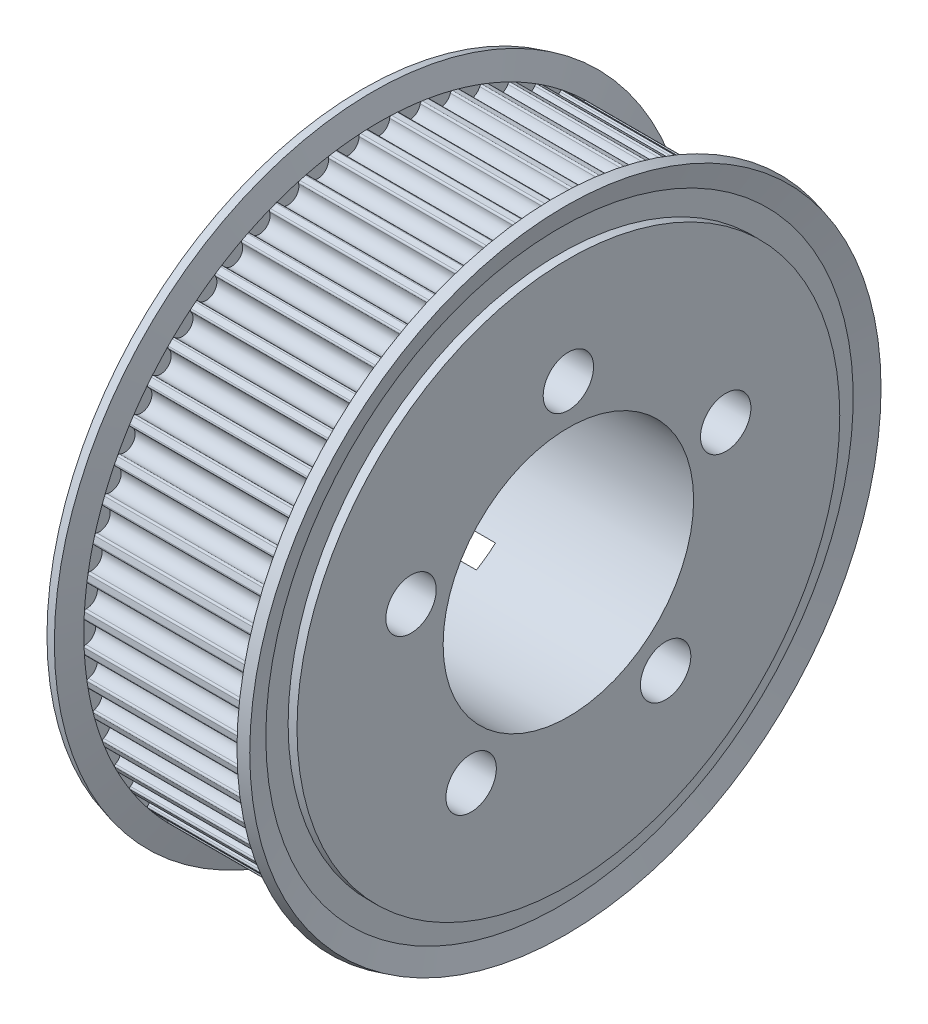
SolidWorks part; units mm, degrees
ref_plane "Front Plane" through (0, 0, 0) normal (0, 0, 1) x (1, 0, 0)
ref_plane "Top Plane" through (0, 0, 0) normal (0, 1, 0) x (1, 0, 0)
ref_plane "Right Plane" through (0, 0, 0) normal (1, 0, 0) x (0, 0, -1)
ref_plane "Plane1" through (0, 0, 0) normal (0, 0, 1) x (1, 0, 0)
sketch "Sketch1" plane through (0, 0, 0) normal (0, 0, 1) x (1, 0, 0)
  line L0 (0, 0) -> (0, 26)
  line L1 (0, 26) -> (0.85, 26)
  line L2 (0.85, 26) -> (0.85, 28.1383)
  line L3 (0.85, 28.1383) -> (0.2865, 30.2412)
  line L4 (0.2865, 30.2412) -> (1.2525, 30.5)
  line L5 (1.2525, 30.5) -> (1.85, 28.27)
  line L6 (1.85, 28.27) -> (18.15, 28.27)
  line L7 (18.15, 28.27) -> (18.7475, 30.5)
  line L8 (18.7475, 30.5) -> (19.7135, 30.2412)
  line L9 (19.7135, 30.2412) -> (19.15, 28.1383)
  line L10 (19.15, 28.1383) -> (19.15, 26)
  line L11 (19.15, 26) -> (20, 26)
  line L12 (20, 26) -> (20, 0)
  line L13 (20, 0) -> (0, 0)
  line L14 (20, 0) -> (0, 0) construction
revolve "Revolve1" add sketch "Sketch1" angle 360 about L14
ref_plane "Plane2" through (10, 0, 0) normal (1, 0, 0) x (0, 0, -1)
sketch "Sketch2" plane through (10, 0, 0) normal (1, 0, 0) x (0, 0, -1)
  line L0 (-1.2204, 28.624) -> (-1.2042, 28.2443)
  line L1 (1.2042, 28.2443) -> (1.2204, 28.624)
  arc A0 (-1.2042, 28.2443) -> (-1.0274, 28.0866) centre (-1.1969, 28.0745) cw
  arc A1 (-1.0274, 28.0866) -> (1.0274, 28.0866) centre (0, 28.16) ccw
  arc A2 (1.0274, 28.0866) -> (1.2042, 28.2443) centre (1.1969, 28.0745) cw
  arc A3 (1.2204, 28.624) -> (-1.2204, 28.624) centre (0, 0) ccw
extrude "Cut-Extrude1" cut sketch "Sketch2" against normal blind 8.15 and the other way blind 8.15
ref_plane "Plane3" through (10, 0, 0) normal (1, 0, 0) x (0, 0, -1)
sketch "Sketch3" plane through (10, 0, 0) normal (1, 0, 0) x (0, 0, -1)
  line L0 (-4.2057, 28.3396) -> (-4.1499, 27.9637)
  line L1 (-1.7547, 28.2155) -> (-1.7783, 28.5948)
  arc A0 (-4.1499, 27.9637) -> (-3.9576, 27.8254) centre (-4.125, 27.7956) cw
  arc A1 (-3.9576, 27.8254) -> (-1.9141, 28.0401) centre (-2.9435, 28.0057) ccw
  arc A2 (-1.9141, 28.0401) -> (-1.7547, 28.2155) centre (-1.7442, 28.0458) cw
  arc A3 (-1.7783, 28.5948) -> (-4.2057, 28.3396) centre (0, 0) ccw
extrude "Cut-Extrude2" cut sketch "Sketch3" against normal blind 8.15 and the other way blind 8.15
ref_plane "Plane4" through (10, 0, 0) normal (1, 0, 0) x (0, 0, -1)
sketch "Sketch4" plane through (10, 0, 0) normal (1, 0, 0) x (0, 0, -1)
  line L0 (-7.145, 27.7448) -> (-7.0502, 27.3768)
  line L1 (-4.6945, 27.8775) -> (-4.7576, 28.2522)
  arc A0 (-7.0502, 27.3768) -> (-6.8445, 27.2592) centre (-7.0078, 27.2121) cw
  arc A1 (-6.8445, 27.2592) -> (-4.8346, 27.6865) centre (-5.8548, 27.5446) ccw
  arc A2 (-4.8346, 27.6865) -> (-4.6945, 27.8775) centre (-4.6662, 27.7099) cw
  arc A3 (-4.7576, 28.2522) -> (-7.145, 27.7448) centre (0, 0) ccw
extrude "Cut-Extrude3" cut sketch "Sketch4" against normal blind 8.15 and the other way blind 8.15
ref_plane "Plane5" through (10, 0, 0) normal (1, 0, 0) x (0, 0, -1)
sketch "Sketch5" plane through (10, 0, 0) normal (1, 0, 0) x (0, 0, -1)
  line L0 (-10.0059, 26.8459) -> (-9.8732, 26.4898)
  line L1 (-7.5827, 27.2341) -> (-7.6847, 27.6002)
  arc A0 (-9.8732, 26.4898) -> (-9.6563, 26.3945) centre (-9.8139, 26.3306) cw
  arc A1 (-9.6563, 26.3945) -> (-7.7021, 27.0294) centre (-8.7019, 26.7818) ccw
  arc A2 (-7.7021, 27.0294) -> (-7.5827, 27.2341) centre (-7.5371, 27.0703) cw
  arc A3 (-7.6847, 27.6002) -> (-10.0059, 26.8459) centre (0, 0) ccw
extrude "Cut-Extrude4" cut sketch "Sketch5" against normal blind 8.15 and the other way blind 8.15
ref_plane "Plane6" through (10, 0, 0) normal (1, 0, 0) x (0, 0, -1)
sketch "Sketch6" plane through (10, 0, 0) normal (1, 0, 0) x (0, 0, -1)
  line L0 (-12.7573, 25.6529) -> (-12.5881, 25.3127)
  line L1 (-10.3879, 26.2923) -> (-10.5276, 26.6457)
  arc A0 (-12.5881, 25.3127) -> (-12.3624, 25.2405) centre (-12.5124, 25.1605) cw
  arc A1 (-12.3624, 25.2405) -> (-10.4853, 26.0763) centre (-11.4537, 25.7254) ccw
  arc A2 (-10.4853, 26.0763) -> (-10.3879, 26.2923) centre (-10.3255, 26.1342) cw
  arc A3 (-10.5276, 26.6457) -> (-12.7573, 25.6529) centre (0, 0) ccw
extrude "Cut-Extrude5" cut sketch "Sketch6" against normal blind 8.15 and the other way blind 8.15
ref_plane "Plane7" through (10, 0, 0) normal (1, 0, 0) x (0, 0, -1)
sketch "Sketch7" plane through (10, 0, 0) normal (1, 0, 0) x (0, 0, -1)
  line L0 (-15.3689, 24.1789) -> (-15.165, 23.8582)
  line L1 (-13.0793, 25.0624) -> (-13.2551, 25.3993)
  arc A0 (-15.165, 23.8582) -> (-14.933, 23.81) centre (-15.0738, 23.7148) cw
  arc A1 (-14.933, 23.81) -> (-13.1536, 24.8374) centre (-14.08, 24.3873) ccw
  arc A2 (-13.1536, 24.8374) -> (-13.0793, 25.0624) centre (-13.0007, 24.9117) cw
  arc A3 (-13.2551, 25.3993) -> (-15.3689, 24.1789) centre (0, 0) ccw
extrude "Cut-Extrude6" cut sketch "Sketch7" against normal blind 8.15 and the other way blind 8.15
ref_plane "Plane8" through (10, 0, 0) normal (1, 0, 0) x (0, 0, -1)
sketch "Sketch8" plane through (10, 0, 0) normal (1, 0, 0) x (0, 0, -1)
  line L0 (-17.8121, 22.44) -> (-17.5758, 22.1423)
  line L1 (-15.6274, 23.558) -> (-15.8375, 23.8746)
  arc A0 (-17.5758, 22.1423) -> (-17.3401, 22.1187) centre (-17.4701, 22.0092) cw
  arc A1 (-17.3401, 22.1187) -> (-15.6777, 23.3264) centre (-16.552, 22.7819) ccw
  arc A2 (-15.6777, 23.3264) -> (-15.6274, 23.558) centre (-15.5334, 23.4163) cw
  arc A3 (-15.8375, 23.8746) -> (-17.8121, 22.44) centre (0, 0) ccw
extrude "Cut-Extrude7" cut sketch "Sketch8" against normal blind 8.15 and the other way blind 8.15
ref_plane "Plane9" through (10, 0, 0) normal (1, 0, 0) x (0, 0, -1)
sketch "Sketch9" plane through (10, 0, 0) normal (1, 0, 0) x (0, 0, -1)
  line L0 (-20.0601, 20.4552) -> (-19.794, 20.1839)
  line L1 (-18.0043, 21.7954) -> (-18.2463, 22.0884)
  arc A0 (-19.794, 20.1839) -> (-19.5571, 20.185) centre (-19.675, 20.0625) cw
  arc A1 (-19.5571, 20.185) -> (-18.0301, 21.5599) centre (-18.8427, 20.927) ccw
  arc A2 (-18.0301, 21.5599) -> (-18.0043, 21.7954) centre (-17.896, 21.6643) cw
  arc A3 (-18.2463, 22.0884) -> (-20.0601, 20.4552) centre (0, 0) ccw
extrude "Cut-Extrude8" cut sketch "Sketch9" against normal blind 8.15 and the other way blind 8.15
ref_plane "Plane10" through (10, 0, 0) normal (1, 0, 0) x (0, 0, -1)
sketch "Sketch10" plane through (10, 0, 0) normal (1, 0, 0) x (0, 0, -1)
  line L0 (-22.0884, 18.2463) -> (-21.7954, 18.0043)
  line L1 (-20.1839, 19.794) -> (-20.4552, 20.0601)
  arc A0 (-21.7954, 18.0043) -> (-21.5599, 18.0301) centre (-21.6643, 17.896) cw
  arc A1 (-21.5599, 18.0301) -> (-20.185, 19.5571) centre (-20.927, 18.8427) ccw
  arc A2 (-20.185, 19.5571) -> (-20.1839, 19.794) centre (-20.0625, 19.675) cw
  arc A3 (-20.4552, 20.0601) -> (-22.0884, 18.2463) centre (0, 0) ccw
extrude "Cut-Extrude9" cut sketch "Sketch10" against normal blind 8.15 and the other way blind 8.15
ref_plane "Plane11" through (10, 0, 0) normal (1, 0, 0) x (0, 0, -1)
sketch "Sketch11" plane through (10, 0, 0) normal (1, 0, 0) x (0, 0, -1)
  line L0 (-23.8746, 15.8375) -> (-23.558, 15.6274)
  line L1 (-22.1423, 17.5758) -> (-22.44, 17.8121)
  arc A0 (-23.558, 15.6274) -> (-23.3264, 15.6777) centre (-23.4163, 15.5334) cw
  arc A1 (-23.3264, 15.6777) -> (-22.1187, 17.3401) centre (-22.7819, 16.552) ccw
  arc A2 (-22.1187, 17.3401) -> (-22.1423, 17.5758) centre (-22.0092, 17.4701) cw
  arc A3 (-22.44, 17.8121) -> (-23.8746, 15.8375) centre (0, 0) ccw
extrude "Cut-Extrude10" cut sketch "Sketch11" against normal blind 8.15 and the other way blind 8.15
ref_plane "Plane12" through (10, 0, 0) normal (1, 0, 0) x (0, 0, -1)
sketch "Sketch12" plane through (10, 0, 0) normal (1, 0, 0) x (0, 0, -1)
  line L0 (-25.3993, 13.2551) -> (-25.0624, 13.0793)
  line L1 (-23.8582, 15.165) -> (-24.1789, 15.3689)
  arc A0 (-25.0624, 13.0793) -> (-24.8374, 13.1536) centre (-24.9117, 13.0007) cw
  arc A1 (-24.8374, 13.1536) -> (-23.81, 14.933) centre (-24.3873, 14.08) ccw
  arc A2 (-23.81, 14.933) -> (-23.8582, 15.165) centre (-23.7148, 15.0738) cw
  arc A3 (-24.1789, 15.3689) -> (-25.3993, 13.2551) centre (0, 0) ccw
extrude "Cut-Extrude11" cut sketch "Sketch12" against normal blind 8.15 and the other way blind 8.15
ref_plane "Plane13" through (10, 0, 0) normal (1, 0, 0) x (0, 0, -1)
sketch "Sketch13" plane through (10, 0, 0) normal (1, 0, 0) x (0, 0, -1)
  line L0 (-26.6457, 10.5276) -> (-26.2923, 10.3879)
  line L1 (-25.3127, 12.5881) -> (-25.6529, 12.7573)
  arc A0 (-26.2923, 10.3879) -> (-26.0763, 10.4853) centre (-26.1342, 10.3255) cw
  arc A1 (-26.0763, 10.4853) -> (-25.2405, 12.3624) centre (-25.7254, 11.4537) ccw
  arc A2 (-25.2405, 12.3624) -> (-25.3127, 12.5881) centre (-25.1605, 12.5124) cw
  arc A3 (-25.6529, 12.7573) -> (-26.6457, 10.5276) centre (0, 0) ccw
extrude "Cut-Extrude12" cut sketch "Sketch13" against normal blind 8.15 and the other way blind 8.15
ref_plane "Plane14" through (10, 0, 0) normal (1, 0, 0) x (0, 0, -1)
sketch "Sketch14" plane through (10, 0, 0) normal (1, 0, 0) x (0, 0, -1)
  line L0 (-27.6002, 7.6847) -> (-27.2341, 7.5827)
  line L1 (-26.4898, 9.8732) -> (-26.8459, 10.0059)
  arc A0 (-27.2341, 7.5827) -> (-27.0294, 7.7021) centre (-27.0703, 7.5371) cw
  arc A1 (-27.0294, 7.7021) -> (-26.3945, 9.6563) centre (-26.7818, 8.7019) ccw
  arc A2 (-26.3945, 9.6563) -> (-26.4898, 9.8732) centre (-26.3306, 9.8139) cw
  arc A3 (-26.8459, 10.0059) -> (-27.6002, 7.6847) centre (0, 0) ccw
extrude "Cut-Extrude13" cut sketch "Sketch14" against normal blind 8.15 and the other way blind 8.15
ref_plane "Plane15" through (10, 0, 0) normal (1, 0, 0) x (0, 0, -1)
sketch "Sketch15" plane through (10, 0, 0) normal (1, 0, 0) x (0, 0, -1)
  line L0 (-28.2522, 4.7576) -> (-27.8775, 4.6945)
  line L1 (-27.3768, 7.0502) -> (-27.7448, 7.145)
  arc A0 (-27.8775, 4.6945) -> (-27.6865, 4.8346) centre (-27.7099, 4.6662) cw
  arc A1 (-27.6865, 4.8346) -> (-27.2592, 6.8445) centre (-27.5446, 5.8548) ccw
  arc A2 (-27.2592, 6.8445) -> (-27.3768, 7.0502) centre (-27.2121, 7.0078) cw
  arc A3 (-27.7448, 7.145) -> (-28.2522, 4.7576) centre (0, 0) ccw
extrude "Cut-Extrude14" cut sketch "Sketch15" against normal blind 8.15 and the other way blind 8.15
ref_plane "Plane16" through (10, 0, 0) normal (1, 0, 0) x (0, 0, -1)
sketch "Sketch16" plane through (10, 0, 0) normal (1, 0, 0) x (0, 0, -1)
  line L0 (-28.5948, 1.7783) -> (-28.2155, 1.7547)
  line L1 (-27.9637, 4.1499) -> (-28.3396, 4.2057)
  arc A0 (-28.2155, 1.7547) -> (-28.0401, 1.9141) centre (-28.0458, 1.7442) cw
  arc A1 (-28.0401, 1.9141) -> (-27.8254, 3.9576) centre (-28.0057, 2.9435) ccw
  arc A2 (-27.8254, 3.9576) -> (-27.9637, 4.1499) centre (-27.7956, 4.125) cw
  arc A3 (-28.3396, 4.2057) -> (-28.5948, 1.7783) centre (0, 0) ccw
extrude "Cut-Extrude15" cut sketch "Sketch16" against normal blind 8.15 and the other way blind 8.15
ref_plane "Plane17" through (10, 0, 0) normal (1, 0, 0) x (0, 0, -1)
sketch "Sketch17" plane through (10, 0, 0) normal (1, 0, 0) x (0, 0, -1)
  line L0 (-28.624, -1.2204) -> (-28.2443, -1.2042)
  line L1 (-28.2443, 1.2042) -> (-28.624, 1.2204)
  arc A0 (-28.2443, -1.2042) -> (-28.0866, -1.0274) centre (-28.0745, -1.1969) cw
  arc A1 (-28.0866, -1.0274) -> (-28.0866, 1.0274) centre (-28.16, 0) ccw
  arc A2 (-28.0866, 1.0274) -> (-28.2443, 1.2042) centre (-28.0745, 1.1969) cw
  arc A3 (-28.624, 1.2204) -> (-28.624, -1.2204) centre (0, 0) ccw
extrude "Cut-Extrude16" cut sketch "Sketch17" against normal blind 8.15 and the other way blind 8.15
ref_plane "Plane18" through (10, 0, 0) normal (1, 0, 0) x (0, 0, -1)
sketch "Sketch18" plane through (10, 0, 0) normal (1, 0, 0) x (0, 0, -1)
  line L0 (-28.3396, -4.2057) -> (-27.9637, -4.1499)
  line L1 (-28.2155, -1.7547) -> (-28.5948, -1.7783)
  arc A0 (-27.9637, -4.1499) -> (-27.8254, -3.9576) centre (-27.7956, -4.125) cw
  arc A1 (-27.8254, -3.9576) -> (-28.0401, -1.9141) centre (-28.0057, -2.9435) ccw
  arc A2 (-28.0401, -1.9141) -> (-28.2155, -1.7547) centre (-28.0458, -1.7442) cw
  arc A3 (-28.5948, -1.7783) -> (-28.3396, -4.2057) centre (0, 0) ccw
extrude "Cut-Extrude17" cut sketch "Sketch18" against normal blind 8.15 and the other way blind 8.15
ref_plane "Plane19" through (10, 0, 0) normal (1, 0, 0) x (0, 0, -1)
sketch "Sketch19" plane through (10, 0, 0) normal (1, 0, 0) x (0, 0, -1)
  line L0 (-27.7448, -7.145) -> (-27.3768, -7.0502)
  line L1 (-27.8775, -4.6945) -> (-28.2522, -4.7576)
  arc A0 (-27.3768, -7.0502) -> (-27.2592, -6.8445) centre (-27.2121, -7.0078) cw
  arc A1 (-27.2592, -6.8445) -> (-27.6865, -4.8346) centre (-27.5446, -5.8548) ccw
  arc A2 (-27.6865, -4.8346) -> (-27.8775, -4.6945) centre (-27.7099, -4.6662) cw
  arc A3 (-28.2522, -4.7576) -> (-27.7448, -7.145) centre (0, 0) ccw
extrude "Cut-Extrude18" cut sketch "Sketch19" against normal blind 8.15 and the other way blind 8.15
ref_plane "Plane20" through (10, 0, 0) normal (1, 0, 0) x (0, 0, -1)
sketch "Sketch20" plane through (10, 0, 0) normal (1, 0, 0) x (0, 0, -1)
  line L0 (-26.8459, -10.0059) -> (-26.4898, -9.8732)
  line L1 (-27.2341, -7.5827) -> (-27.6002, -7.6847)
  arc A0 (-26.4898, -9.8732) -> (-26.3945, -9.6563) centre (-26.3306, -9.8139) cw
  arc A1 (-26.3945, -9.6563) -> (-27.0294, -7.7021) centre (-26.7818, -8.7019) ccw
  arc A2 (-27.0294, -7.7021) -> (-27.2341, -7.5827) centre (-27.0703, -7.5371) cw
  arc A3 (-27.6002, -7.6847) -> (-26.8459, -10.0059) centre (0, 0) ccw
extrude "Cut-Extrude19" cut sketch "Sketch20" against normal blind 8.15 and the other way blind 8.15
ref_plane "Plane21" through (10, 0, 0) normal (1, 0, 0) x (0, 0, -1)
sketch "Sketch21" plane through (10, 0, 0) normal (1, 0, 0) x (0, 0, -1)
  line L0 (-25.6529, -12.7573) -> (-25.3127, -12.5881)
  line L1 (-26.2923, -10.3879) -> (-26.6457, -10.5276)
  arc A0 (-25.3127, -12.5881) -> (-25.2405, -12.3624) centre (-25.1605, -12.5124) cw
  arc A1 (-25.2405, -12.3624) -> (-26.0763, -10.4853) centre (-25.7254, -11.4537) ccw
  arc A2 (-26.0763, -10.4853) -> (-26.2923, -10.3879) centre (-26.1342, -10.3255) cw
  arc A3 (-26.6457, -10.5276) -> (-25.6529, -12.7573) centre (0, 0) ccw
extrude "Cut-Extrude20" cut sketch "Sketch21" against normal blind 8.15 and the other way blind 8.15
ref_plane "Plane22" through (10, 0, 0) normal (1, 0, 0) x (0, 0, -1)
sketch "Sketch22" plane through (10, 0, 0) normal (1, 0, 0) x (0, 0, -1)
  line L0 (-24.1789, -15.3689) -> (-23.8582, -15.165)
  line L1 (-25.0624, -13.0793) -> (-25.3993, -13.2551)
  arc A0 (-23.8582, -15.165) -> (-23.81, -14.933) centre (-23.7148, -15.0738) cw
  arc A1 (-23.81, -14.933) -> (-24.8374, -13.1536) centre (-24.3873, -14.08) ccw
  arc A2 (-24.8374, -13.1536) -> (-25.0624, -13.0793) centre (-24.9117, -13.0007) cw
  arc A3 (-25.3993, -13.2551) -> (-24.1789, -15.3689) centre (0, 0) ccw
extrude "Cut-Extrude21" cut sketch "Sketch22" against normal blind 8.15 and the other way blind 8.15
ref_plane "Plane23" through (10, 0, 0) normal (1, 0, 0) x (0, 0, -1)
sketch "Sketch23" plane through (10, 0, 0) normal (1, 0, 0) x (0, 0, -1)
  line L0 (-22.44, -17.8121) -> (-22.1423, -17.5758)
  line L1 (-23.558, -15.6274) -> (-23.8746, -15.8375)
  arc A0 (-22.1423, -17.5758) -> (-22.1187, -17.3401) centre (-22.0092, -17.4701) cw
  arc A1 (-22.1187, -17.3401) -> (-23.3264, -15.6777) centre (-22.7819, -16.552) ccw
  arc A2 (-23.3264, -15.6777) -> (-23.558, -15.6274) centre (-23.4163, -15.5334) cw
  arc A3 (-23.8746, -15.8375) -> (-22.44, -17.8121) centre (0, 0) ccw
extrude "Cut-Extrude22" cut sketch "Sketch23" against normal blind 8.15 and the other way blind 8.15
ref_plane "Plane24" through (10, 0, 0) normal (1, 0, 0) x (0, 0, -1)
sketch "Sketch24" plane through (10, 0, 0) normal (1, 0, 0) x (0, 0, -1)
  line L0 (-20.4552, -20.0601) -> (-20.1839, -19.794)
  line L1 (-21.7954, -18.0043) -> (-22.0884, -18.2463)
  arc A0 (-20.1839, -19.794) -> (-20.185, -19.5571) centre (-20.0625, -19.675) cw
  arc A1 (-20.185, -19.5571) -> (-21.5599, -18.0301) centre (-20.927, -18.8427) ccw
  arc A2 (-21.5599, -18.0301) -> (-21.7954, -18.0043) centre (-21.6643, -17.896) cw
  arc A3 (-22.0884, -18.2463) -> (-20.4552, -20.0601) centre (0, 0) ccw
extrude "Cut-Extrude23" cut sketch "Sketch24" against normal blind 8.15 and the other way blind 8.15
ref_plane "Plane25" through (10, 0, 0) normal (1, 0, 0) x (0, 0, -1)
sketch "Sketch25" plane through (10, 0, 0) normal (1, 0, 0) x (0, 0, -1)
  line L0 (-18.2463, -22.0884) -> (-18.0043, -21.7954)
  line L1 (-19.794, -20.1839) -> (-20.0601, -20.4552)
  arc A0 (-18.0043, -21.7954) -> (-18.0301, -21.5599) centre (-17.896, -21.6643) cw
  arc A1 (-18.0301, -21.5599) -> (-19.5571, -20.185) centre (-18.8427, -20.927) ccw
  arc A2 (-19.5571, -20.185) -> (-19.794, -20.1839) centre (-19.675, -20.0625) cw
  arc A3 (-20.0601, -20.4552) -> (-18.2463, -22.0884) centre (0, 0) ccw
extrude "Cut-Extrude24" cut sketch "Sketch25" against normal blind 8.15 and the other way blind 8.15
ref_plane "Plane26" through (10, 0, 0) normal (1, 0, 0) x (0, 0, -1)
sketch "Sketch26" plane through (10, 0, 0) normal (1, 0, 0) x (0, 0, -1)
  line L0 (-15.8375, -23.8746) -> (-15.6274, -23.558)
  line L1 (-17.5758, -22.1423) -> (-17.8121, -22.44)
  arc A0 (-15.6274, -23.558) -> (-15.6777, -23.3264) centre (-15.5334, -23.4163) cw
  arc A1 (-15.6777, -23.3264) -> (-17.3401, -22.1187) centre (-16.552, -22.7819) ccw
  arc A2 (-17.3401, -22.1187) -> (-17.5758, -22.1423) centre (-17.4701, -22.0092) cw
  arc A3 (-17.8121, -22.44) -> (-15.8375, -23.8746) centre (0, 0) ccw
extrude "Cut-Extrude25" cut sketch "Sketch26" against normal blind 8.15 and the other way blind 8.15
ref_plane "Plane27" through (10, 0, 0) normal (1, 0, 0) x (0, 0, -1)
sketch "Sketch27" plane through (10, 0, 0) normal (1, 0, 0) x (0, 0, -1)
  line L0 (-13.2551, -25.3993) -> (-13.0793, -25.0624)
  line L1 (-15.165, -23.8582) -> (-15.3689, -24.1789)
  arc A0 (-13.0793, -25.0624) -> (-13.1536, -24.8374) centre (-13.0007, -24.9117) cw
  arc A1 (-13.1536, -24.8374) -> (-14.933, -23.81) centre (-14.08, -24.3873) ccw
  arc A2 (-14.933, -23.81) -> (-15.165, -23.8582) centre (-15.0738, -23.7148) cw
  arc A3 (-15.3689, -24.1789) -> (-13.2551, -25.3993) centre (0, 0) ccw
extrude "Cut-Extrude26" cut sketch "Sketch27" against normal blind 8.15 and the other way blind 8.15
ref_plane "Plane28" through (10, 0, 0) normal (1, 0, 0) x (0, 0, -1)
sketch "Sketch28" plane through (10, 0, 0) normal (1, 0, 0) x (0, 0, -1)
  line L0 (-10.5276, -26.6457) -> (-10.3879, -26.2923)
  line L1 (-12.5881, -25.3127) -> (-12.7573, -25.6529)
  arc A0 (-10.3879, -26.2923) -> (-10.4853, -26.0763) centre (-10.3255, -26.1342) cw
  arc A1 (-10.4853, -26.0763) -> (-12.3624, -25.2405) centre (-11.4537, -25.7254) ccw
  arc A2 (-12.3624, -25.2405) -> (-12.5881, -25.3127) centre (-12.5124, -25.1605) cw
  arc A3 (-12.7573, -25.6529) -> (-10.5276, -26.6457) centre (0, 0) ccw
extrude "Cut-Extrude27" cut sketch "Sketch28" against normal blind 8.15 and the other way blind 8.15
ref_plane "Plane29" through (10, 0, 0) normal (1, 0, 0) x (0, 0, -1)
sketch "Sketch29" plane through (10, 0, 0) normal (1, 0, 0) x (0, 0, -1)
  line L0 (-7.6847, -27.6002) -> (-7.5827, -27.2341)
  line L1 (-9.8732, -26.4898) -> (-10.0059, -26.8459)
  arc A0 (-7.5827, -27.2341) -> (-7.7021, -27.0294) centre (-7.5371, -27.0703) cw
  arc A1 (-7.7021, -27.0294) -> (-9.6563, -26.3945) centre (-8.7019, -26.7818) ccw
  arc A2 (-9.6563, -26.3945) -> (-9.8732, -26.4898) centre (-9.8139, -26.3306) cw
  arc A3 (-10.0059, -26.8459) -> (-7.6847, -27.6002) centre (0, 0) ccw
extrude "Cut-Extrude28" cut sketch "Sketch29" against normal blind 8.15 and the other way blind 8.15
ref_plane "Plane30" through (10, 0, 0) normal (1, 0, 0) x (0, 0, -1)
sketch "Sketch30" plane through (10, 0, 0) normal (1, 0, 0) x (0, 0, -1)
  line L0 (-4.7576, -28.2522) -> (-4.6945, -27.8775)
  line L1 (-7.0502, -27.3768) -> (-7.145, -27.7448)
  arc A0 (-4.6945, -27.8775) -> (-4.8346, -27.6865) centre (-4.6662, -27.7099) cw
  arc A1 (-4.8346, -27.6865) -> (-6.8445, -27.2592) centre (-5.8548, -27.5446) ccw
  arc A2 (-6.8445, -27.2592) -> (-7.0502, -27.3768) centre (-7.0078, -27.2121) cw
  arc A3 (-7.145, -27.7448) -> (-4.7576, -28.2522) centre (0, 0) ccw
extrude "Cut-Extrude29" cut sketch "Sketch30" against normal blind 8.15 and the other way blind 8.15
ref_plane "Plane31" through (10, 0, 0) normal (1, 0, 0) x (0, 0, -1)
sketch "Sketch31" plane through (10, 0, 0) normal (1, 0, 0) x (0, 0, -1)
  line L0 (-1.7783, -28.5948) -> (-1.7547, -28.2155)
  line L1 (-4.1499, -27.9637) -> (-4.2057, -28.3396)
  arc A0 (-1.7547, -28.2155) -> (-1.9141, -28.0401) centre (-1.7442, -28.0458) cw
  arc A1 (-1.9141, -28.0401) -> (-3.9576, -27.8254) centre (-2.9435, -28.0057) ccw
  arc A2 (-3.9576, -27.8254) -> (-4.1499, -27.9637) centre (-4.125, -27.7956) cw
  arc A3 (-4.2057, -28.3396) -> (-1.7783, -28.5948) centre (0, 0) ccw
extrude "Cut-Extrude30" cut sketch "Sketch31" against normal blind 8.15 and the other way blind 8.15
ref_plane "Plane32" through (10, 0, 0) normal (1, 0, 0) x (0, 0, -1)
sketch "Sketch32" plane through (10, 0, 0) normal (1, 0, 0) x (0, 0, -1)
  line L0 (1.2204, -28.624) -> (1.2042, -28.2443)
  line L1 (-1.2042, -28.2443) -> (-1.2204, -28.624)
  arc A0 (1.2042, -28.2443) -> (1.0274, -28.0866) centre (1.1969, -28.0745) cw
  arc A1 (1.0274, -28.0866) -> (-1.0274, -28.0866) centre (0, -28.16) ccw
  arc A2 (-1.0274, -28.0866) -> (-1.2042, -28.2443) centre (-1.1969, -28.0745) cw
  arc A3 (-1.2204, -28.624) -> (1.2204, -28.624) centre (0, 0) ccw
extrude "Cut-Extrude31" cut sketch "Sketch32" against normal blind 8.15 and the other way blind 8.15
ref_plane "Plane33" through (10, 0, 0) normal (1, 0, 0) x (0, 0, -1)
sketch "Sketch33" plane through (10, 0, 0) normal (1, 0, 0) x (0, 0, -1)
  line L0 (4.2057, -28.3396) -> (4.1499, -27.9637)
  line L1 (1.7547, -28.2155) -> (1.7783, -28.5948)
  arc A0 (4.1499, -27.9637) -> (3.9576, -27.8254) centre (4.125, -27.7956) cw
  arc A1 (3.9576, -27.8254) -> (1.9141, -28.0401) centre (2.9435, -28.0057) ccw
  arc A2 (1.9141, -28.0401) -> (1.7547, -28.2155) centre (1.7442, -28.0458) cw
  arc A3 (1.7783, -28.5948) -> (4.2057, -28.3396) centre (0, 0) ccw
extrude "Cut-Extrude32" cut sketch "Sketch33" against normal blind 8.15 and the other way blind 8.15
ref_plane "Plane34" through (10, 0, 0) normal (1, 0, 0) x (0, 0, -1)
sketch "Sketch34" plane through (10, 0, 0) normal (1, 0, 0) x (0, 0, -1)
  line L0 (7.145, -27.7448) -> (7.0502, -27.3768)
  line L1 (4.6945, -27.8775) -> (4.7576, -28.2522)
  arc A0 (7.0502, -27.3768) -> (6.8445, -27.2592) centre (7.0078, -27.2121) cw
  arc A1 (6.8445, -27.2592) -> (4.8346, -27.6865) centre (5.8548, -27.5446) ccw
  arc A2 (4.8346, -27.6865) -> (4.6945, -27.8775) centre (4.6662, -27.7099) cw
  arc A3 (4.7576, -28.2522) -> (7.145, -27.7448) centre (0, 0) ccw
extrude "Cut-Extrude33" cut sketch "Sketch34" against normal blind 8.15 and the other way blind 8.15
ref_plane "Plane35" through (10, 0, 0) normal (1, 0, 0) x (0, 0, -1)
sketch "Sketch35" plane through (10, 0, 0) normal (1, 0, 0) x (0, 0, -1)
  line L0 (10.0059, -26.8459) -> (9.8732, -26.4898)
  line L1 (7.5827, -27.2341) -> (7.6847, -27.6002)
  arc A0 (9.8732, -26.4898) -> (9.6563, -26.3945) centre (9.8139, -26.3306) cw
  arc A1 (9.6563, -26.3945) -> (7.7021, -27.0294) centre (8.7019, -26.7818) ccw
  arc A2 (7.7021, -27.0294) -> (7.5827, -27.2341) centre (7.5371, -27.0703) cw
  arc A3 (7.6847, -27.6002) -> (10.0059, -26.8459) centre (0, 0) ccw
extrude "Cut-Extrude34" cut sketch "Sketch35" against normal blind 8.15 and the other way blind 8.15
ref_plane "Plane36" through (10, 0, 0) normal (1, 0, 0) x (0, 0, -1)
sketch "Sketch36" plane through (10, 0, 0) normal (1, 0, 0) x (0, 0, -1)
  line L0 (12.7573, -25.6529) -> (12.5881, -25.3127)
  line L1 (10.3879, -26.2923) -> (10.5276, -26.6457)
  arc A0 (12.5881, -25.3127) -> (12.3624, -25.2405) centre (12.5124, -25.1605) cw
  arc A1 (12.3624, -25.2405) -> (10.4853, -26.0763) centre (11.4537, -25.7254) ccw
  arc A2 (10.4853, -26.0763) -> (10.3879, -26.2923) centre (10.3255, -26.1342) cw
  arc A3 (10.5276, -26.6457) -> (12.7573, -25.6529) centre (0, 0) ccw
extrude "Cut-Extrude35" cut sketch "Sketch36" against normal blind 8.15 and the other way blind 8.15
ref_plane "Plane37" through (10, 0, 0) normal (1, 0, 0) x (0, 0, -1)
sketch "Sketch37" plane through (10, 0, 0) normal (1, 0, 0) x (0, 0, -1)
  line L0 (15.3689, -24.1789) -> (15.165, -23.8582)
  line L1 (13.0793, -25.0624) -> (13.2551, -25.3993)
  arc A0 (15.165, -23.8582) -> (14.933, -23.81) centre (15.0738, -23.7148) cw
  arc A1 (14.933, -23.81) -> (13.1536, -24.8374) centre (14.08, -24.3873) ccw
  arc A2 (13.1536, -24.8374) -> (13.0793, -25.0624) centre (13.0007, -24.9117) cw
  arc A3 (13.2551, -25.3993) -> (15.3689, -24.1789) centre (0, 0) ccw
extrude "Cut-Extrude36" cut sketch "Sketch37" against normal blind 8.15 and the other way blind 8.15
ref_plane "Plane38" through (10, 0, 0) normal (1, 0, 0) x (0, 0, -1)
sketch "Sketch38" plane through (10, 0, 0) normal (1, 0, 0) x (0, 0, -1)
  line L0 (17.8121, -22.44) -> (17.5758, -22.1423)
  line L1 (15.6274, -23.558) -> (15.8375, -23.8746)
  arc A0 (17.5758, -22.1423) -> (17.3401, -22.1187) centre (17.4701, -22.0092) cw
  arc A1 (17.3401, -22.1187) -> (15.6777, -23.3264) centre (16.552, -22.7819) ccw
  arc A2 (15.6777, -23.3264) -> (15.6274, -23.558) centre (15.5334, -23.4163) cw
  arc A3 (15.8375, -23.8746) -> (17.8121, -22.44) centre (0, 0) ccw
extrude "Cut-Extrude37" cut sketch "Sketch38" against normal blind 8.15 and the other way blind 8.15
ref_plane "Plane39" through (10, 0, 0) normal (1, 0, 0) x (0, 0, -1)
sketch "Sketch39" plane through (10, 0, 0) normal (1, 0, 0) x (0, 0, -1)
  line L0 (20.0601, -20.4552) -> (19.794, -20.1839)
  line L1 (18.0043, -21.7954) -> (18.2463, -22.0884)
  arc A0 (19.794, -20.1839) -> (19.5571, -20.185) centre (19.675, -20.0625) cw
  arc A1 (19.5571, -20.185) -> (18.0301, -21.5599) centre (18.8427, -20.927) ccw
  arc A2 (18.0301, -21.5599) -> (18.0043, -21.7954) centre (17.896, -21.6643) cw
  arc A3 (18.2463, -22.0884) -> (20.0601, -20.4552) centre (0, 0) ccw
extrude "Cut-Extrude38" cut sketch "Sketch39" against normal blind 8.15 and the other way blind 8.15
ref_plane "Plane40" through (10, 0, 0) normal (1, 0, 0) x (0, 0, -1)
sketch "Sketch40" plane through (10, 0, 0) normal (1, 0, 0) x (0, 0, -1)
  line L0 (22.0884, -18.2463) -> (21.7954, -18.0043)
  line L1 (20.1839, -19.794) -> (20.4552, -20.0601)
  arc A0 (21.7954, -18.0043) -> (21.5599, -18.0301) centre (21.6643, -17.896) cw
  arc A1 (21.5599, -18.0301) -> (20.185, -19.5571) centre (20.927, -18.8427) ccw
  arc A2 (20.185, -19.5571) -> (20.1839, -19.794) centre (20.0625, -19.675) cw
  arc A3 (20.4552, -20.0601) -> (22.0884, -18.2463) centre (0, 0) ccw
extrude "Cut-Extrude39" cut sketch "Sketch40" against normal blind 8.15 and the other way blind 8.15
ref_plane "Plane41" through (10, 0, 0) normal (1, 0, 0) x (0, 0, -1)
sketch "Sketch41" plane through (10, 0, 0) normal (1, 0, 0) x (0, 0, -1)
  line L0 (23.8746, -15.8375) -> (23.558, -15.6274)
  line L1 (22.1423, -17.5758) -> (22.44, -17.8121)
  arc A0 (23.558, -15.6274) -> (23.3264, -15.6777) centre (23.4163, -15.5334) cw
  arc A1 (23.3264, -15.6777) -> (22.1187, -17.3401) centre (22.7819, -16.552) ccw
  arc A2 (22.1187, -17.3401) -> (22.1423, -17.5758) centre (22.0092, -17.4701) cw
  arc A3 (22.44, -17.8121) -> (23.8746, -15.8375) centre (0, 0) ccw
extrude "Cut-Extrude40" cut sketch "Sketch41" against normal blind 8.15 and the other way blind 8.15
ref_plane "Plane42" through (10, 0, 0) normal (1, 0, 0) x (0, 0, -1)
sketch "Sketch42" plane through (10, 0, 0) normal (1, 0, 0) x (0, 0, -1)
  line L0 (25.3993, -13.2551) -> (25.0624, -13.0793)
  line L1 (23.8582, -15.165) -> (24.1789, -15.3689)
  arc A0 (25.0624, -13.0793) -> (24.8374, -13.1536) centre (24.9117, -13.0007) cw
  arc A1 (24.8374, -13.1536) -> (23.81, -14.933) centre (24.3873, -14.08) ccw
  arc A2 (23.81, -14.933) -> (23.8582, -15.165) centre (23.7148, -15.0738) cw
  arc A3 (24.1789, -15.3689) -> (25.3993, -13.2551) centre (0, 0) ccw
extrude "Cut-Extrude41" cut sketch "Sketch42" against normal blind 8.15 and the other way blind 8.15
ref_plane "Plane43" through (10, 0, 0) normal (1, 0, 0) x (0, 0, -1)
sketch "Sketch43" plane through (10, 0, 0) normal (1, 0, 0) x (0, 0, -1)
  line L0 (26.6457, -10.5276) -> (26.2923, -10.3879)
  line L1 (25.3127, -12.5881) -> (25.6529, -12.7573)
  arc A0 (26.2923, -10.3879) -> (26.0763, -10.4853) centre (26.1342, -10.3255) cw
  arc A1 (26.0763, -10.4853) -> (25.2405, -12.3624) centre (25.7254, -11.4537) ccw
  arc A2 (25.2405, -12.3624) -> (25.3127, -12.5881) centre (25.1605, -12.5124) cw
  arc A3 (25.6529, -12.7573) -> (26.6457, -10.5276) centre (0, 0) ccw
extrude "Cut-Extrude42" cut sketch "Sketch43" against normal blind 8.15 and the other way blind 8.15
ref_plane "Plane44" through (10, 0, 0) normal (1, 0, 0) x (0, 0, -1)
sketch "Sketch44" plane through (10, 0, 0) normal (1, 0, 0) x (0, 0, -1)
  line L0 (27.6002, -7.6847) -> (27.2341, -7.5827)
  line L1 (26.4898, -9.8732) -> (26.8459, -10.0059)
  arc A0 (27.2341, -7.5827) -> (27.0294, -7.7021) centre (27.0703, -7.5371) cw
  arc A1 (27.0294, -7.7021) -> (26.3945, -9.6563) centre (26.7818, -8.7019) ccw
  arc A2 (26.3945, -9.6563) -> (26.4898, -9.8732) centre (26.3306, -9.8139) cw
  arc A3 (26.8459, -10.0059) -> (27.6002, -7.6847) centre (0, 0) ccw
extrude "Cut-Extrude43" cut sketch "Sketch44" against normal blind 8.15 and the other way blind 8.15
ref_plane "Plane45" through (10, 0, 0) normal (1, 0, 0) x (0, 0, -1)
sketch "Sketch45" plane through (10, 0, 0) normal (1, 0, 0) x (0, 0, -1)
  line L0 (28.2522, -4.7576) -> (27.8775, -4.6945)
  line L1 (27.3768, -7.0502) -> (27.7448, -7.145)
  arc A0 (27.8775, -4.6945) -> (27.6865, -4.8346) centre (27.7099, -4.6662) cw
  arc A1 (27.6865, -4.8346) -> (27.2592, -6.8445) centre (27.5446, -5.8548) ccw
  arc A2 (27.2592, -6.8445) -> (27.3768, -7.0502) centre (27.2121, -7.0078) cw
  arc A3 (27.7448, -7.145) -> (28.2522, -4.7576) centre (0, 0) ccw
extrude "Cut-Extrude44" cut sketch "Sketch45" against normal blind 8.15 and the other way blind 8.15
ref_plane "Plane46" through (10, 0, 0) normal (1, 0, 0) x (0, 0, -1)
sketch "Sketch46" plane through (10, 0, 0) normal (1, 0, 0) x (0, 0, -1)
  line L0 (28.5948, -1.7783) -> (28.2155, -1.7547)
  line L1 (27.9637, -4.1499) -> (28.3396, -4.2057)
  arc A0 (28.2155, -1.7547) -> (28.0401, -1.9141) centre (28.0458, -1.7442) cw
  arc A1 (28.0401, -1.9141) -> (27.8254, -3.9576) centre (28.0057, -2.9435) ccw
  arc A2 (27.8254, -3.9576) -> (27.9637, -4.1499) centre (27.7956, -4.125) cw
  arc A3 (28.3396, -4.2057) -> (28.5948, -1.7783) centre (0, 0) ccw
extrude "Cut-Extrude45" cut sketch "Sketch46" against normal blind 8.15 and the other way blind 8.15
ref_plane "Plane47" through (10, 0, 0) normal (1, 0, 0) x (0, 0, -1)
sketch "Sketch47" plane through (10, 0, 0) normal (1, 0, 0) x (0, 0, -1)
  line L0 (28.624, 1.2204) -> (28.2443, 1.2042)
  line L1 (28.2443, -1.2042) -> (28.624, -1.2204)
  arc A0 (28.2443, 1.2042) -> (28.0866, 1.0274) centre (28.0745, 1.1969) cw
  arc A1 (28.0866, 1.0274) -> (28.0866, -1.0274) centre (28.16, 0) ccw
  arc A2 (28.0866, -1.0274) -> (28.2443, -1.2042) centre (28.0745, -1.1969) cw
  arc A3 (28.624, -1.2204) -> (28.624, 1.2204) centre (0, 0) ccw
extrude "Cut-Extrude46" cut sketch "Sketch47" against normal blind 8.15 and the other way blind 8.15
ref_plane "Plane48" through (10, 0, 0) normal (1, 0, 0) x (0, 0, -1)
sketch "Sketch48" plane through (10, 0, 0) normal (1, 0, 0) x (0, 0, -1)
  line L0 (28.3396, 4.2057) -> (27.9637, 4.1499)
  line L1 (28.2155, 1.7547) -> (28.5948, 1.7783)
  arc A0 (27.9637, 4.1499) -> (27.8254, 3.9576) centre (27.7956, 4.125) cw
  arc A1 (27.8254, 3.9576) -> (28.0401, 1.9141) centre (28.0057, 2.9435) ccw
  arc A2 (28.0401, 1.9141) -> (28.2155, 1.7547) centre (28.0458, 1.7442) cw
  arc A3 (28.5948, 1.7783) -> (28.3396, 4.2057) centre (0, 0) ccw
extrude "Cut-Extrude47" cut sketch "Sketch48" against normal blind 8.15 and the other way blind 8.15
ref_plane "Plane49" through (10, 0, 0) normal (1, 0, 0) x (0, 0, -1)
sketch "Sketch49" plane through (10, 0, 0) normal (1, 0, 0) x (0, 0, -1)
  line L0 (27.7448, 7.145) -> (27.3768, 7.0502)
  line L1 (27.8775, 4.6945) -> (28.2522, 4.7576)
  arc A0 (27.3768, 7.0502) -> (27.2592, 6.8445) centre (27.2121, 7.0078) cw
  arc A1 (27.2592, 6.8445) -> (27.6865, 4.8346) centre (27.5446, 5.8548) ccw
  arc A2 (27.6865, 4.8346) -> (27.8775, 4.6945) centre (27.7099, 4.6662) cw
  arc A3 (28.2522, 4.7576) -> (27.7448, 7.145) centre (0, 0) ccw
extrude "Cut-Extrude48" cut sketch "Sketch49" against normal blind 8.15 and the other way blind 8.15
ref_plane "Plane50" through (10, 0, 0) normal (1, 0, 0) x (0, 0, -1)
sketch "Sketch50" plane through (10, 0, 0) normal (1, 0, 0) x (0, 0, -1)
  line L0 (26.8459, 10.0059) -> (26.4898, 9.8732)
  line L1 (27.2341, 7.5827) -> (27.6002, 7.6847)
  arc A0 (26.4898, 9.8732) -> (26.3945, 9.6563) centre (26.3306, 9.8139) cw
  arc A1 (26.3945, 9.6563) -> (27.0294, 7.7021) centre (26.7818, 8.7019) ccw
  arc A2 (27.0294, 7.7021) -> (27.2341, 7.5827) centre (27.0703, 7.5371) cw
  arc A3 (27.6002, 7.6847) -> (26.8459, 10.0059) centre (0, 0) ccw
extrude "Cut-Extrude49" cut sketch "Sketch50" against normal blind 8.15 and the other way blind 8.15
ref_plane "Plane51" through (10, 0, 0) normal (1, 0, 0) x (0, 0, -1)
sketch "Sketch51" plane through (10, 0, 0) normal (1, 0, 0) x (0, 0, -1)
  line L0 (25.6529, 12.7573) -> (25.3127, 12.5881)
  line L1 (26.2923, 10.3879) -> (26.6457, 10.5276)
  arc A0 (25.3127, 12.5881) -> (25.2405, 12.3624) centre (25.1605, 12.5124) cw
  arc A1 (25.2405, 12.3624) -> (26.0763, 10.4853) centre (25.7254, 11.4537) ccw
  arc A2 (26.0763, 10.4853) -> (26.2923, 10.3879) centre (26.1342, 10.3255) cw
  arc A3 (26.6457, 10.5276) -> (25.6529, 12.7573) centre (0, 0) ccw
extrude "Cut-Extrude50" cut sketch "Sketch51" against normal blind 8.15 and the other way blind 8.15
ref_plane "Plane52" through (10, 0, 0) normal (1, 0, 0) x (0, 0, -1)
sketch "Sketch52" plane through (10, 0, 0) normal (1, 0, 0) x (0, 0, -1)
  line L0 (24.1789, 15.3689) -> (23.8582, 15.165)
  line L1 (25.0624, 13.0793) -> (25.3993, 13.2551)
  arc A0 (23.8582, 15.165) -> (23.81, 14.933) centre (23.7148, 15.0738) cw
  arc A1 (23.81, 14.933) -> (24.8374, 13.1536) centre (24.3873, 14.08) ccw
  arc A2 (24.8374, 13.1536) -> (25.0624, 13.0793) centre (24.9117, 13.0007) cw
  arc A3 (25.3993, 13.2551) -> (24.1789, 15.3689) centre (0, 0) ccw
extrude "Cut-Extrude51" cut sketch "Sketch52" against normal blind 8.15 and the other way blind 8.15
ref_plane "Plane53" through (10, 0, 0) normal (1, 0, 0) x (0, 0, -1)
sketch "Sketch53" plane through (10, 0, 0) normal (1, 0, 0) x (0, 0, -1)
  line L0 (22.44, 17.8121) -> (22.1423, 17.5758)
  line L1 (23.558, 15.6274) -> (23.8746, 15.8375)
  arc A0 (22.1423, 17.5758) -> (22.1187, 17.3401) centre (22.0092, 17.4701) cw
  arc A1 (22.1187, 17.3401) -> (23.3264, 15.6777) centre (22.7819, 16.552) ccw
  arc A2 (23.3264, 15.6777) -> (23.558, 15.6274) centre (23.4163, 15.5334) cw
  arc A3 (23.8746, 15.8375) -> (22.44, 17.8121) centre (0, 0) ccw
extrude "Cut-Extrude52" cut sketch "Sketch53" against normal blind 8.15 and the other way blind 8.15
ref_plane "Plane54" through (10, 0, 0) normal (1, 0, 0) x (0, 0, -1)
sketch "Sketch54" plane through (10, 0, 0) normal (1, 0, 0) x (0, 0, -1)
  line L0 (20.4552, 20.0601) -> (20.1839, 19.794)
  line L1 (21.7954, 18.0043) -> (22.0884, 18.2463)
  arc A0 (20.1839, 19.794) -> (20.185, 19.5571) centre (20.0625, 19.675) cw
  arc A1 (20.185, 19.5571) -> (21.5599, 18.0301) centre (20.927, 18.8427) ccw
  arc A2 (21.5599, 18.0301) -> (21.7954, 18.0043) centre (21.6643, 17.896) cw
  arc A3 (22.0884, 18.2463) -> (20.4552, 20.0601) centre (0, 0) ccw
extrude "Cut-Extrude53" cut sketch "Sketch54" against normal blind 8.15 and the other way blind 8.15
ref_plane "Plane55" through (10, 0, 0) normal (1, 0, 0) x (0, 0, -1)
sketch "Sketch55" plane through (10, 0, 0) normal (1, 0, 0) x (0, 0, -1)
  line L0 (18.2463, 22.0884) -> (18.0043, 21.7954)
  line L1 (19.794, 20.1839) -> (20.0601, 20.4552)
  arc A0 (18.0043, 21.7954) -> (18.0301, 21.5599) centre (17.896, 21.6643) cw
  arc A1 (18.0301, 21.5599) -> (19.5571, 20.185) centre (18.8427, 20.927) ccw
  arc A2 (19.5571, 20.185) -> (19.794, 20.1839) centre (19.675, 20.0625) cw
  arc A3 (20.0601, 20.4552) -> (18.2463, 22.0884) centre (0, 0) ccw
extrude "Cut-Extrude54" cut sketch "Sketch55" against normal blind 8.15 and the other way blind 8.15
ref_plane "Plane56" through (10, 0, 0) normal (1, 0, 0) x (0, 0, -1)
sketch "Sketch56" plane through (10, 0, 0) normal (1, 0, 0) x (0, 0, -1)
  line L0 (15.8375, 23.8746) -> (15.6274, 23.558)
  line L1 (17.5758, 22.1423) -> (17.8121, 22.44)
  arc A0 (15.6274, 23.558) -> (15.6777, 23.3264) centre (15.5334, 23.4163) cw
  arc A1 (15.6777, 23.3264) -> (17.3401, 22.1187) centre (16.552, 22.7819) ccw
  arc A2 (17.3401, 22.1187) -> (17.5758, 22.1423) centre (17.4701, 22.0092) cw
  arc A3 (17.8121, 22.44) -> (15.8375, 23.8746) centre (0, 0) ccw
extrude "Cut-Extrude55" cut sketch "Sketch56" against normal blind 8.15 and the other way blind 8.15
ref_plane "Plane57" through (10, 0, 0) normal (1, 0, 0) x (0, 0, -1)
sketch "Sketch57" plane through (10, 0, 0) normal (1, 0, 0) x (0, 0, -1)
  line L0 (13.2551, 25.3993) -> (13.0793, 25.0624)
  line L1 (15.165, 23.8582) -> (15.3689, 24.1789)
  arc A0 (13.0793, 25.0624) -> (13.1536, 24.8374) centre (13.0007, 24.9117) cw
  arc A1 (13.1536, 24.8374) -> (14.933, 23.81) centre (14.08, 24.3873) ccw
  arc A2 (14.933, 23.81) -> (15.165, 23.8582) centre (15.0738, 23.7148) cw
  arc A3 (15.3689, 24.1789) -> (13.2551, 25.3993) centre (0, 0) ccw
extrude "Cut-Extrude56" cut sketch "Sketch57" against normal blind 8.15 and the other way blind 8.15
ref_plane "Plane58" through (10, 0, 0) normal (1, 0, 0) x (0, 0, -1)
sketch "Sketch58" plane through (10, 0, 0) normal (1, 0, 0) x (0, 0, -1)
  line L0 (10.5276, 26.6457) -> (10.3879, 26.2923)
  line L1 (12.5881, 25.3127) -> (12.7573, 25.6529)
  arc A0 (10.3879, 26.2923) -> (10.4853, 26.0763) centre (10.3255, 26.1342) cw
  arc A1 (10.4853, 26.0763) -> (12.3624, 25.2405) centre (11.4537, 25.7254) ccw
  arc A2 (12.3624, 25.2405) -> (12.5881, 25.3127) centre (12.5124, 25.1605) cw
  arc A3 (12.7573, 25.6529) -> (10.5276, 26.6457) centre (0, 0) ccw
extrude "Cut-Extrude57" cut sketch "Sketch58" against normal blind 8.15 and the other way blind 8.15
ref_plane "Plane59" through (10, 0, 0) normal (1, 0, 0) x (0, 0, -1)
sketch "Sketch59" plane through (10, 0, 0) normal (1, 0, 0) x (0, 0, -1)
  line L0 (7.6847, 27.6002) -> (7.5827, 27.2341)
  line L1 (9.8732, 26.4898) -> (10.0059, 26.8459)
  arc A0 (7.5827, 27.2341) -> (7.7021, 27.0294) centre (7.5371, 27.0703) cw
  arc A1 (7.7021, 27.0294) -> (9.6563, 26.3945) centre (8.7019, 26.7818) ccw
  arc A2 (9.6563, 26.3945) -> (9.8732, 26.4898) centre (9.8139, 26.3306) cw
  arc A3 (10.0059, 26.8459) -> (7.6847, 27.6002) centre (0, 0) ccw
extrude "Cut-Extrude58" cut sketch "Sketch59" against normal blind 8.15 and the other way blind 8.15
ref_plane "Plane60" through (10, 0, 0) normal (1, 0, 0) x (0, 0, -1)
sketch "Sketch60" plane through (10, 0, 0) normal (1, 0, 0) x (0, 0, -1)
  line L0 (4.7576, 28.2522) -> (4.6945, 27.8775)
  line L1 (7.0502, 27.3768) -> (7.145, 27.7448)
  arc A0 (4.6945, 27.8775) -> (4.8346, 27.6865) centre (4.6662, 27.7099) cw
  arc A1 (4.8346, 27.6865) -> (6.8445, 27.2592) centre (5.8548, 27.5446) ccw
  arc A2 (6.8445, 27.2592) -> (7.0502, 27.3768) centre (7.0078, 27.2121) cw
  arc A3 (7.145, 27.7448) -> (4.7576, 28.2522) centre (0, 0) ccw
extrude "Cut-Extrude59" cut sketch "Sketch60" against normal blind 8.15 and the other way blind 8.15
ref_plane "Plane61" through (10, 0, 0) normal (1, 0, 0) x (0, 0, -1)
sketch "Sketch61" plane through (10, 0, 0) normal (1, 0, 0) x (0, 0, -1)
  line L0 (1.7783, 28.5948) -> (1.7547, 28.2155)
  line L1 (4.1499, 27.9637) -> (4.2057, 28.3396)
  arc A0 (1.7547, 28.2155) -> (1.9141, 28.0401) centre (1.7442, 28.0458) cw
  arc A1 (1.9141, 28.0401) -> (3.9576, 27.8254) centre (2.9435, 28.0057) ccw
  arc A2 (3.9576, 27.8254) -> (4.1499, 27.9637) centre (4.125, 27.7956) cw
  arc A3 (4.2057, 28.3396) -> (1.7783, 28.5948) centre (0, 0) ccw
extrude "Cut-Extrude60" cut sketch "Sketch61" against normal blind 8.15 and the other way blind 8.15
ref_plane "Plane62" through (0, 0, 0) normal (0, 0, 1) x (1, 0, 0)
sketch "Sketch62" plane through (0, 0, 0) normal (0, 0, 1) x (1, 0, 0)
  line L0 (0, 0) -> (0, 12)
  line L1 (0, 12) -> (20, 12)
  line L2 (20, 12) -> (20, 0)
  line L3 (20, 0) -> (0, 0)
  line L4 (20, 0) -> (0, 0) construction
revolve "Cut-Revolve1" cut sketch "Sketch62" angle 360 about L4
sketch "Sketch63" plane through (0, 0, 0) normal (-1, 0, 0) x (0, 0, 1)
  circle A0 centre (0, 15.85) radius 2.413
  circle A2 centre (15.0742, 4.8979) radius 2.413
  circle A3 centre (9.3164, -12.8229) radius 2.413
  circle A4 centre (-9.3164, -12.8229) radius 2.413
  circle A5 centre (-15.0742, 4.8979) radius 2.413
  point P13 (0, 0)
  dimension "D1" = 5
  dimension "D2" = 4.826
extrude "Cut-Extrude61" cut sketch "Sketch63" against normal through all
sketch "Sketch64" plane through (0, 0, 0) normal (-1, 0, 0) x (0, 0, 1)
  circle A0 centre (0, 15.85) radius 4.064
  circle A1 centre (15.0742, 4.8979) radius 4.064
  circle A2 centre (9.3164, -12.8229) radius 4.064
  circle A3 centre (-9.3164, -12.8229) radius 4.064
  circle A4 centre (-15.0742, 4.8979) radius 4.064
  point P13 (0, 0)
  dimension "D1" = 8.128
  dimension "D2" = 5
extrude "Cut-Extrude62" cut sketch "Sketch64" against normal blind 5.08
